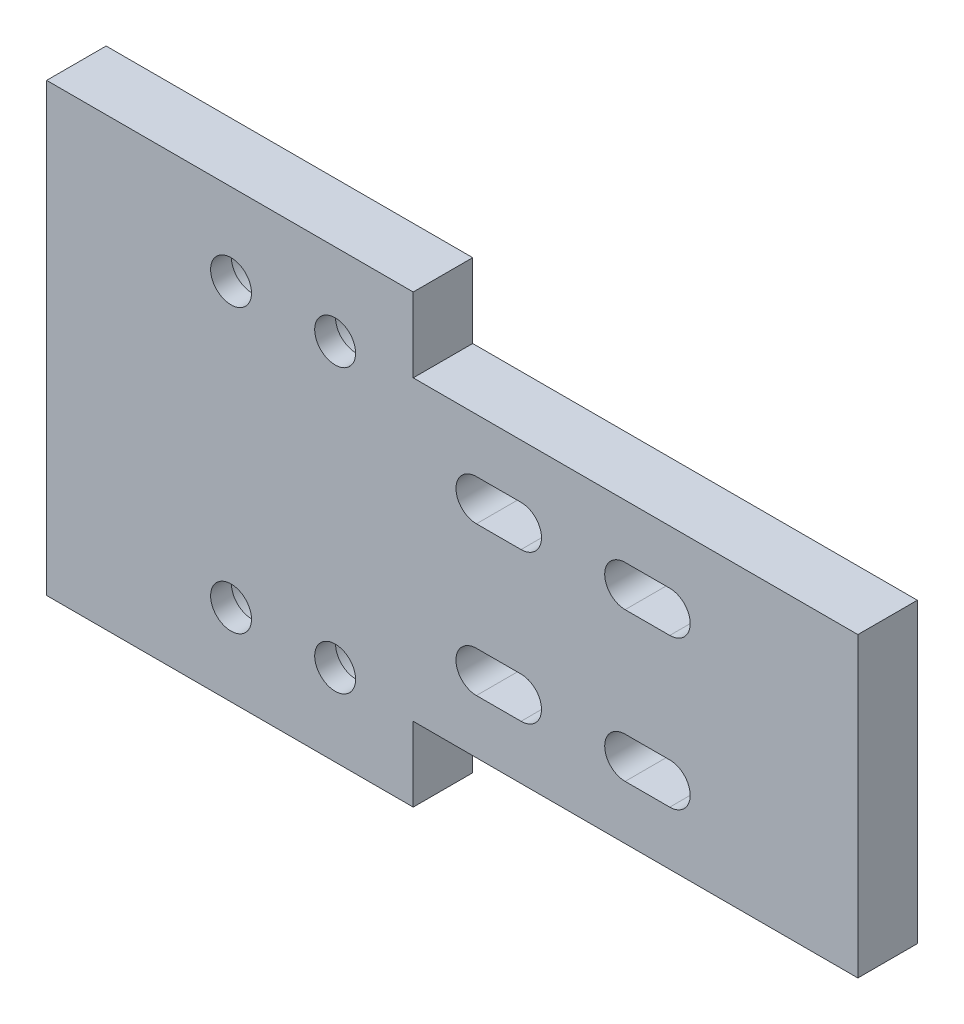
SolidWorks part; units mm, degrees
ref_plane "Front Plane" through (0, 0, 0) normal (0, 0, 1) x (1, 0, 0)
ref_plane "Top Plane" through (0, 0, 0) normal (0, 1, 0) x (1, 0, 0)
ref_plane "Right Plane" through (0, 0, 0) normal (1, 0, 0) x (0, 0, -1)
ref_plane "Plane1" through (0, 0, 238) normal (0, 0, 1) x (1, 0, 0)
sketch "Sketch1" plane through (0, 0, 238) normal (0, 0, 1) x (1, 0, 0)
  line L0 (227.2, 280) -> (336.3, 280)
  line L1 (336.3, 280) -> (336.3, 320)
  line L2 (336.3, 320) -> (227.2, 320)
  line L3 (227.2, 320) -> (227.2, 280)
  line L4 (285, 287.25) -> (291, 287.25)
  line L5 (291, 292.75) -> (285, 292.75)
  line L6 (285, 307.25) -> (291, 307.25)
  line L7 (291, 312.75) -> (285, 312.75)
  line L8 (305, 287.25) -> (311, 287.25)
  line L9 (311, 292.75) -> (305, 292.75)
  line L10 (305, 307.25) -> (311, 307.25)
  line L11 (311, 312.75) -> (305, 312.75)
  arc A0 (291, 287.25) -> (291, 292.75) centre (291, 290) ccw
  arc A1 (285, 292.75) -> (285, 287.25) centre (285, 290) ccw
  arc A2 (291, 307.25) -> (291, 312.75) centre (291, 310) ccw
  arc A3 (285, 312.75) -> (285, 307.25) centre (285, 310) ccw
  arc A4 (311, 287.25) -> (311, 292.75) centre (311, 290) ccw
  arc A5 (305, 292.75) -> (305, 287.25) centre (305, 290) ccw
  arc A6 (311, 307.25) -> (311, 312.75) centre (311, 310) ccw
  arc A7 (305, 312.75) -> (305, 307.25) centre (305, 310) ccw
extrude "Boss-Extrude1" add sketch "Sketch1" along normal blind 8
sketch "Sketch2" plane through (0, 0, 238) normal (0, 0, 1) x (1, 0, 0)
  line L0 (227.2, 270) -> (276.5, 270)
  line L1 (276.5, 270) -> (276.5, 280)
  line L2 (276.5, 280) -> (227.2, 280)
  line L3 (227.2, 280) -> (227.2, 270)
extrude "Boss-Extrude2" add sketch "Sketch2" along normal blind 8
sketch "Sketch3" plane through (0, 0, 238) normal (0, 0, 1) x (1, 0, 0)
  line L0 (227.2, 320) -> (276.5, 320)
  line L1 (276.5, 320) -> (276.5, 330)
  line L2 (276.5, 330) -> (227.2, 330)
  line L3 (227.2, 330) -> (227.2, 320)
extrude "Boss-Extrude3" add sketch "Sketch3" along normal blind 8
sketch "Sketch4" plane through (0, 0, 238) normal (0, 0, 1) x (1, 0, 0)
  circle A0 centre (252, 281) radius 2.75
  circle A1 centre (252, 319) radius 2.75
  circle A2 centre (266, 281) radius 2.75
  circle A3 centre (266, 319) radius 2.75
extrude "Cut-Extrude1" cut sketch "Sketch4" along normal blind 8
sketch "Sketch5" plane through (0, 0, 238) normal (0, 0, 1) x (1, 0, 0)
  circle A0 centre (252, 281) radius 5
  circle A1 centre (252, 319) radius 5
  circle A2 centre (266, 281) radius 5
  circle A3 centre (266, 319) radius 5
extrude "Cut-Extrude2" cut sketch "Sketch5" along normal blind 5.2
